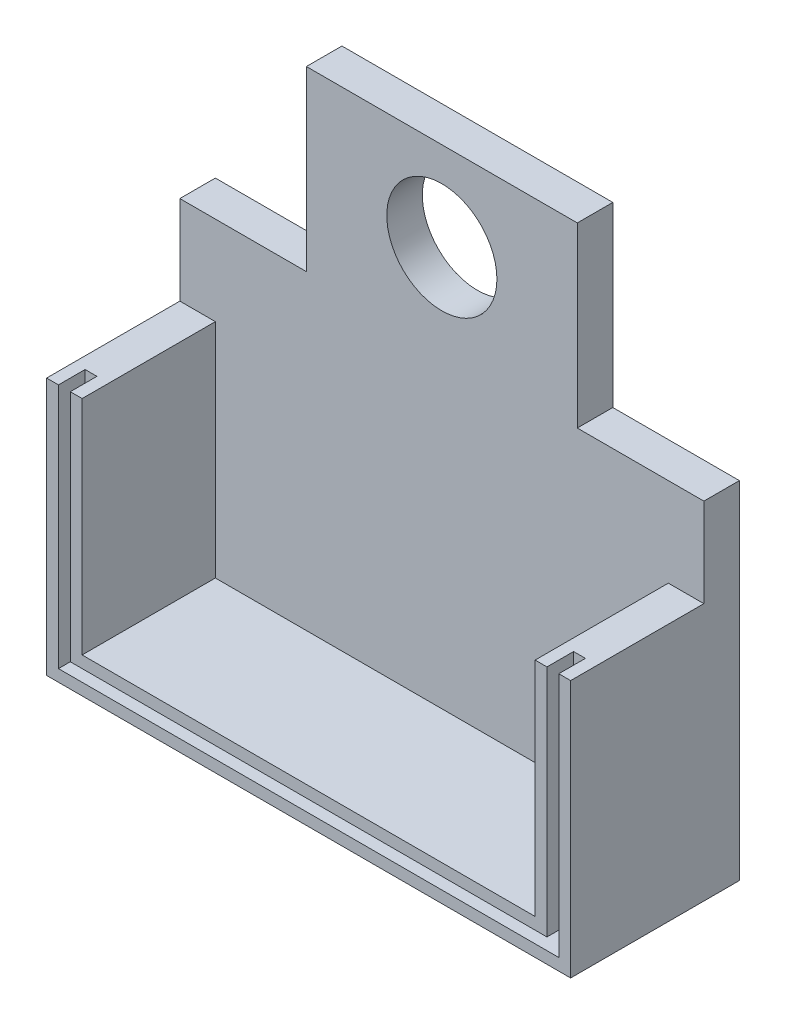
SolidWorks part; units mm, degrees
ref_plane "Płaszczyzna przednia" through (0, 0, 0) normal (0, 0, 1) x (1, 0, 0)
ref_plane "Płaszczyzna górna" through (0, 0, 0) normal (0, 1, 0) x (1, 0, 0)
ref_plane "Płaszczyzna prawa" through (0, 0, 0) normal (1, 0, 0) x (0, 0, -1)
sketch "Sketch1" plane through (0, 0, 0) normal (0, 0, 1) x (1, 0, 0)
  line L1 (-15.25, -10) -> (15.25, -10)
  line L2 (-15.25, -10) -> (-15.25, 10)
  line L3 (-15.25, 10) -> (15.25, 10)
  line L4 (15.25, -10) -> (15.25, 10)
  line L5 (-15.25, -10) -> (15.25, 10) construction
  line L6 (-15.25, 10) -> (15.25, -10) construction
  circle A0 centre (0, 0) radius 6.2
  point P0 (0, 0)
  dimension "D1" = 30.5
  dimension "D2" = 20
extrude "Boss-Extrude1" add sketch "Sketch1" along normal blind 4
sketch "Sketch2" plane through (0, -10, 0) normal (0, -1, 0) x (1, 0, 0)
  line L0 (-15.25, 4) -> (15.25, 0) construction
  line L1 (15.25, 0) -> (15.25, 4) construction
  line L2 (15.25, 4) -> (-15.25, 0) construction
  line L3 (-15.25, 0) -> (-15.25, 4) construction
  line L5 (-29.5, 0) -> (29.5, 0)
  line L6 (-29.5, 0) -> (-29.5, 4)
  line L7 (-29.5, 4) -> (29.5, 4)
  line L8 (29.5, 0) -> (29.5, 4)
  line L9 (-29.5, 0) -> (29.5, 4) construction
  line L10 (-29.5, 4) -> (29.5, 0) construction
  point P6 (0, 2)
  dimension "D1" = 59
extrude "Boss-Extrude2" add sketch "Sketch2" along normal blind 35
sketch "Sketch4" plane through (0, -45, 0) normal (0, -1, 0) x (1, 0, 0)
  line L1 (-29.5, 4) -> (29.5, 4)
  line L2 (-29.5, 4) -> (-29.5, 0)
  line L3 (-29.5, 0) -> (29.5, 0)
  line L4 (29.5, 4) -> (29.5, 0)
extrude "Boss-Extrude3" add sketch "Sketch4" along normal blind 4
sketch "Sketch5" plane through (0, 0, 4) normal (0, 0, 1) x (1, 0, 0)
  line L0 (29.5, -49) -> (29.5, -10) construction
  line L1 (-29.5, -49) -> (29.5, -49)
  line L2 (-29.5, -49) -> (-29.5, -45)
  line L3 (-29.5, -45) -> (29.5, -45)
  line L4 (29.5, -49) -> (29.5, -45)
  line L6 (-29.5, -45) -> (-25.5, -45)
  line L7 (-29.5, -45) -> (-29.5, -20)
  line L8 (-29.5, -20) -> (-25.5, -20)
  line L9 (-25.5, -45) -> (-25.5, -20)
  line L10 (29.5, -45) -> (25.5, -45)
  line L11 (29.5, -45) -> (29.5, -20)
  line L12 (29.5, -20) -> (25.5, -20)
  line L13 (25.5, -45) -> (25.5, -20)
  line M5 (-29.5, -10) -> (-29.5, -49)
  line M6 (-29.5, -49) -> (29.5, -49)
  line M7 (29.5, -49) -> (29.5, -10)
  dimension "D1" = 4
  dimension "D2" = 4
  dimension "D3" = 25
  dimension "D4" = 4
  dimension "D5" = 25
extrude "Boss-Extrude4" add sketch "Sketch5" along normal blind 15 contours L3 L9 L8 M5 | L3 M5 M6 M7 | L13 L3 L12 M7
sketch "Sketch6" plane through (0, 0, 19) normal (0, 0, 1) x (1, 0, 0)
  line L0 (-29.5, -20) -> (-25.5, -20) construction
  line L1 (-28.1667, -20) -> (-26.8333, -20)
  line L2 (-28.1667, -20) -> (-28.1667, -47.6667)
  line L3 (-28.1667, -47.6667) -> (-26.8333, -47.6667)
  line L4 (-26.8333, -20) -> (-26.8333, -47.6667)
  line L5 (-29.5, -20) -> (-29.5, -49) construction
  line L6 (-29.5, -49) -> (29.5, -49) construction
  line L7 (29.5, -49) -> (29.5, -20) construction
  line L8 (-26.8333, -47.6667) -> (28.1667, -47.6667)
  line L9 (-26.8333, -47.6667) -> (-26.8333, -46.3333)
  line L10 (-26.8333, -46.3333) -> (28.1667, -46.3333)
  line L11 (28.1667, -47.6667) -> (28.1667, -46.3333)
  line L12 (29.5, -20) -> (25.5, -20) construction
  line L13 (28.1667, -46.3333) -> (26.8333, -46.3333)
  line L14 (28.1667, -46.3333) -> (28.1667, -20)
  line L15 (28.1667, -20) -> (26.8333, -20)
  line L16 (26.8333, -46.3333) -> (26.8333, -20)
  line M9 (29.5, -20) -> (25.5, -20)
  line M13 (-25.5, -20) -> (-29.5, -20)
  dimension "D1" = 1.3333
  dimension "D2" = 1.3333
  dimension "D3" = 1.3333
  dimension "D4" = 1.3333
  dimension "D5" = 1.3333
  dimension "D6" = 1.3333
extrude "Cut-Extrude1" cut sketch "Sketch6" against normal blind 3 contours L4 L2 L3 M13 | L8 L11 L10 L4 | L16 L10 L14 M9
